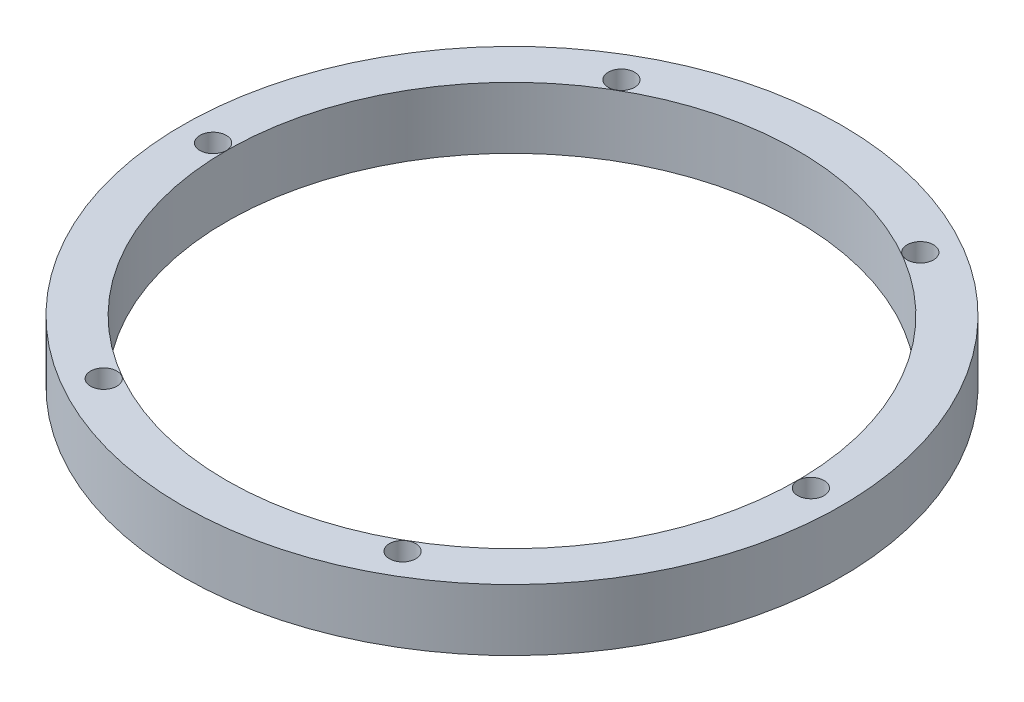
SolidWorks part; units mm, degrees
material "Acrylic (Medium-high impact)"
ref_plane "Front Plane" through (0, 0, 0) normal (0, 0, 1) x (1, 0, 0)
ref_plane "Top Plane" through (0, 0, 0) normal (0, 1, 0) x (1, 0, 0)
ref_plane "Right Plane" through (0, 0, 0) normal (1, 0, 0) x (0, 0, -1)
sketch "Sketch1" plane through (0, 0, 0) normal (0, 1, 0) x (1, 0, 0)
  line L0 (0, 0) -> (88.676, 0) construction
  line L1 (88.676, 0) -> (-95.0922, 0) construction
  line L2 (0, 0) -> (37.1099, -64.2763) construction
  line L3 (37.1099, -64.2763) -> (-35.0592, 60.7243) construction
  line L4 (-44.2878, -76.7087) -> (0, 0) construction
  line L5 (0, 0) -> (36.8411, 63.8106) construction
  circle A0 centre (0, 0) radius 32.5
  circle A1 centre (0, 0) radius 37.5
  circle A2 centre (0, 0) radius 34.01 construction
  circle A3 centre (17.005, -29.4535) radius 1.5
  circle A4 centre (-17.005, -29.4535) radius 1.5
  circle A5 centre (-34.01, 0) radius 1.5
  circle A6 centre (-17.005, 29.4535) radius 1.5
  circle A7 centre (17.005, 29.4535) radius 1.5
  circle A8 centre (34.01, 0) radius 1.5
  dimension "D1" = 60
  dimension "D2" = 60
extrude "Boss-Extrude1" add sketch "Sketch1" along normal blind 7
